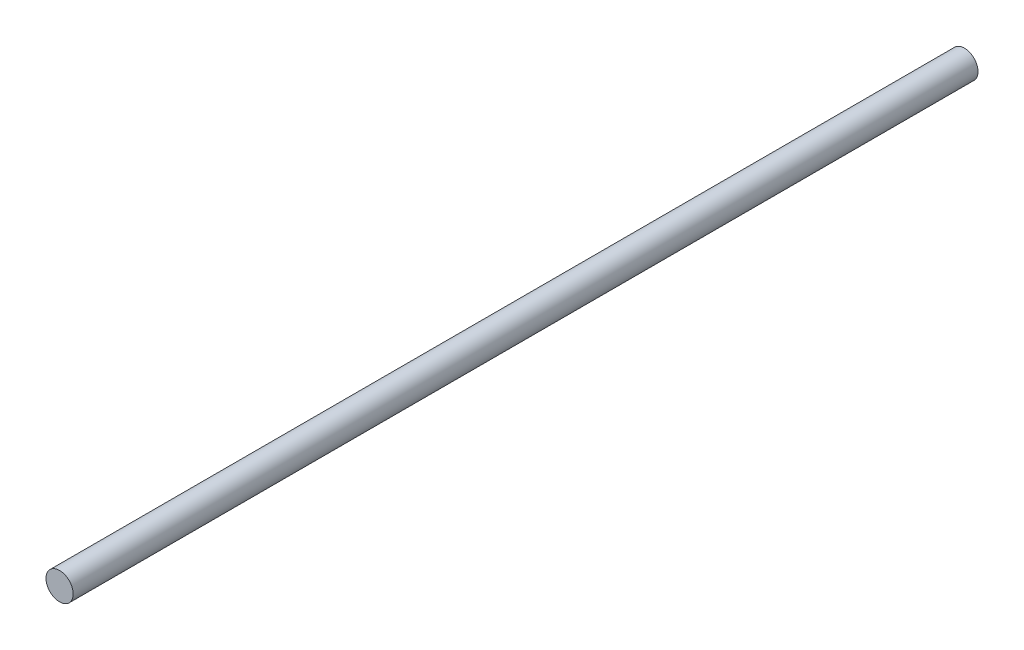
SolidWorks part; units mm, degrees
ref_plane "Front Plane" through (0, 0, 0) normal (0, 0, 1) x (1, 0, 0)
ref_plane "Top Plane" through (0, 0, 0) normal (0, 1, 0) x (1, 0, 0)
ref_plane "Right Plane" through (0, 0, 0) normal (1, 0, 0) x (0, 0, -1)
sketch "Sketch1" plane through (0, 0, 0) normal (0, 0, 1) x (1, 0, 0)
  circle A0 centre (0, 0) radius 6
extrude "Boss-Extrude1" add sketch "Sketch1" along normal blind 399
scale "Scale1" bodies to scale 101 scale about origin uniform scaling yes scale factor 0.5
